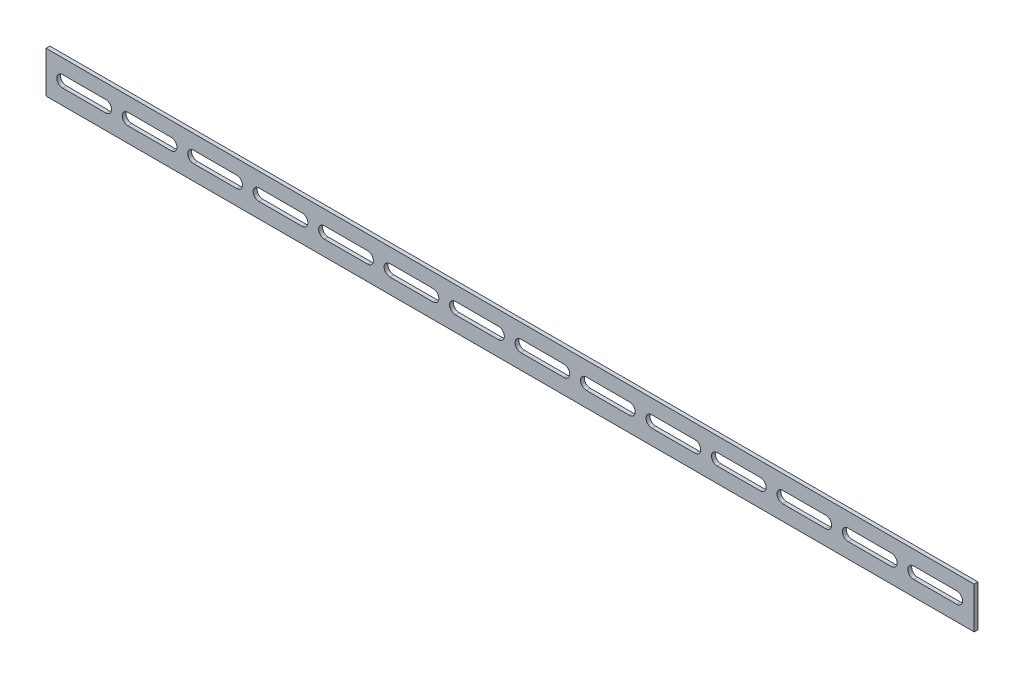
SolidWorks part; units mm, degrees
ref_plane "正面" through (0, 0, 0) normal (0, 0, 1) x (1, 0, 0)
ref_plane "平面" through (0, 0, 0) normal (0, 1, 0) x (1, 0, 0)
ref_plane "右側面" through (0, 0, 0) normal (1, 0, 0) x (0, 0, -1)
sketch "ｽｹｯﾁ1" plane through (0, 0, 0) normal (0, 0, 1) x (1, 0, 0)
  line L0 (-270, 12.8818) -> (-244, 12.8818) construction
  line L1 (-280, 25.1642) -> (280, 25.1642)
  line L2 (-280, 25.1642) -> (-280, 0.1642)
  line L3 (-280, 0.1642) -> (280, 0.1642)
  line L4 (280, 25.1642) -> (280, 0.1642)
  line L5 (-270, 16.3818) -> (-244, 16.3818)
  line L6 (-270, 9.3818) -> (-244, 9.3818)
  line L7 (-230.5, 12.8818) -> (-204.5, 12.8818) construction
  line L8 (-230.5, 16.3818) -> (-204.5, 16.3818)
  line L9 (-230.5, 9.3818) -> (-204.5, 9.3818)
  line L10 (-191, 12.8818) -> (-165, 12.8818) construction
  line L11 (-191, 16.3818) -> (-165, 16.3818)
  line L12 (-191, 9.3818) -> (-165, 9.3818)
  line L13 (-151.5, 12.8818) -> (-125.5, 12.8818) construction
  line L14 (-151.5, 16.3818) -> (-125.5, 16.3818)
  line L15 (-151.5, 9.3818) -> (-125.5, 9.3818)
  line L16 (-112, 12.8818) -> (-86, 12.8818) construction
  line L17 (-112, 16.3818) -> (-86, 16.3818)
  line L18 (-112, 9.3818) -> (-86, 9.3818)
  line L19 (-72.5, 12.8818) -> (-46.5, 12.8818) construction
  line L20 (-72.5, 16.3818) -> (-46.5, 16.3818)
  line L21 (-72.5, 9.3818) -> (-46.5, 9.3818)
  line L22 (-33, 12.8818) -> (-7, 12.8818) construction
  line L23 (-33, 16.3818) -> (-7, 16.3818)
  line L24 (-33, 9.3818) -> (-7, 9.3818)
  line L25 (6.5, 12.8818) -> (32.5, 12.8818) construction
  line L26 (6.5, 16.3818) -> (32.5, 16.3818)
  line L27 (6.5, 9.3818) -> (32.5, 9.3818)
  line L28 (46, 12.8818) -> (72, 12.8818) construction
  line L29 (46, 16.3818) -> (72, 16.3818)
  line L30 (46, 9.3818) -> (72, 9.3818)
  line L31 (85.5, 12.8818) -> (111.5, 12.8818) construction
  line L32 (85.5, 16.3818) -> (111.5, 16.3818)
  line L33 (85.5, 9.3818) -> (111.5, 9.3818)
  line L34 (125, 12.8818) -> (151, 12.8818) construction
  line L35 (125, 16.3818) -> (151, 16.3818)
  line L36 (125, 9.3818) -> (151, 9.3818)
  line L37 (164.5, 12.8818) -> (190.5, 12.8818) construction
  line L38 (164.5, 16.3818) -> (190.5, 16.3818)
  line L39 (164.5, 9.3818) -> (190.5, 9.3818)
  line L40 (204, 12.8818) -> (230, 12.8818) construction
  line L41 (204, 16.3818) -> (230, 16.3818)
  line L42 (204, 9.3818) -> (230, 9.3818)
  line L43 (243.5, 12.8818) -> (269.5, 12.8818) construction
  line L44 (243.5, 16.3818) -> (269.5, 16.3818)
  line L45 (243.5, 9.3818) -> (269.5, 9.3818)
  arc A0 (-270, 16.3818) -> (-270, 9.3818) centre (-270, 12.8818) ccw
  arc A1 (-244, 9.3818) -> (-244, 16.3818) centre (-244, 12.8818) ccw
  arc A2 (-230.5, 16.3818) -> (-230.5, 9.3818) centre (-230.5, 12.8818) ccw
  arc A3 (-204.5, 9.3818) -> (-204.5, 16.3818) centre (-204.5, 12.8818) ccw
  arc A4 (-191, 16.3818) -> (-191, 9.3818) centre (-191, 12.8818) ccw
  arc A5 (-165, 9.3818) -> (-165, 16.3818) centre (-165, 12.8818) ccw
  arc A6 (-151.5, 16.3818) -> (-151.5, 9.3818) centre (-151.5, 12.8818) ccw
  arc A7 (-125.5, 9.3818) -> (-125.5, 16.3818) centre (-125.5, 12.8818) ccw
  arc A8 (-112, 16.3818) -> (-112, 9.3818) centre (-112, 12.8818) ccw
  arc A9 (-86, 9.3818) -> (-86, 16.3818) centre (-86, 12.8818) ccw
  arc A10 (-72.5, 16.3818) -> (-72.5, 9.3818) centre (-72.5, 12.8818) ccw
  arc A11 (-46.5, 9.3818) -> (-46.5, 16.3818) centre (-46.5, 12.8818) ccw
  arc A12 (-33, 16.3818) -> (-33, 9.3818) centre (-33, 12.8818) ccw
  arc A13 (-7, 9.3818) -> (-7, 16.3818) centre (-7, 12.8818) ccw
  arc A14 (6.5, 16.3818) -> (6.5, 9.3818) centre (6.5, 12.8818) ccw
  arc A15 (32.5, 9.3818) -> (32.5, 16.3818) centre (32.5, 12.8818) ccw
  arc A16 (46, 16.3818) -> (46, 9.3818) centre (46, 12.8818) ccw
  arc A17 (72, 9.3818) -> (72, 16.3818) centre (72, 12.8818) ccw
  arc A18 (85.5, 16.3818) -> (85.5, 9.3818) centre (85.5, 12.8818) ccw
  arc A19 (111.5, 9.3818) -> (111.5, 16.3818) centre (111.5, 12.8818) ccw
  arc A20 (125, 16.3818) -> (125, 9.3818) centre (125, 12.8818) ccw
  arc A21 (151, 9.3818) -> (151, 16.3818) centre (151, 12.8818) ccw
  arc A22 (164.5, 16.3818) -> (164.5, 9.3818) centre (164.5, 12.8818) ccw
  arc A23 (190.5, 9.3818) -> (190.5, 16.3818) centre (190.5, 12.8818) ccw
  arc A24 (204, 16.3818) -> (204, 9.3818) centre (204, 12.8818) ccw
  arc A25 (230, 9.3818) -> (230, 16.3818) centre (230, 12.8818) ccw
  arc A26 (243.5, 16.3818) -> (243.5, 9.3818) centre (243.5, 12.8818) ccw
  arc A27 (269.5, 9.3818) -> (269.5, 16.3818) centre (269.5, 12.8818) ccw
  point P0 (0, 0)
  point P8 (-257, 12.8818)
  point P16 (-217.5, 12.8818)
  point P23 (-178, 12.8818)
  point P30 (-138.5, 12.8818)
  point P37 (-99, 12.8818)
  point P44 (-59.5, 12.8818)
  point P51 (-20, 12.8818)
  point P58 (19.5, 12.8818)
  point P65 (59, 12.8818)
  point P72 (98.5, 12.8818)
  point P79 (138, 12.8818)
  point P86 (177.5, 12.8818)
  point P93 (217, 12.8818)
  point P100 (256.5, 12.8818)
  dimension "D5" = 7
  dimension "D1" = 560
  dimension "D2" = 280
  dimension "D3" = 25
  dimension "D4" = 26
  dimension "D6" = 10
  dimension "D7" = 14
extrude "ﾎﾞｽ - 押し出し1" add sketch "ｽｹｯﾁ1" along normal blind 2.3
